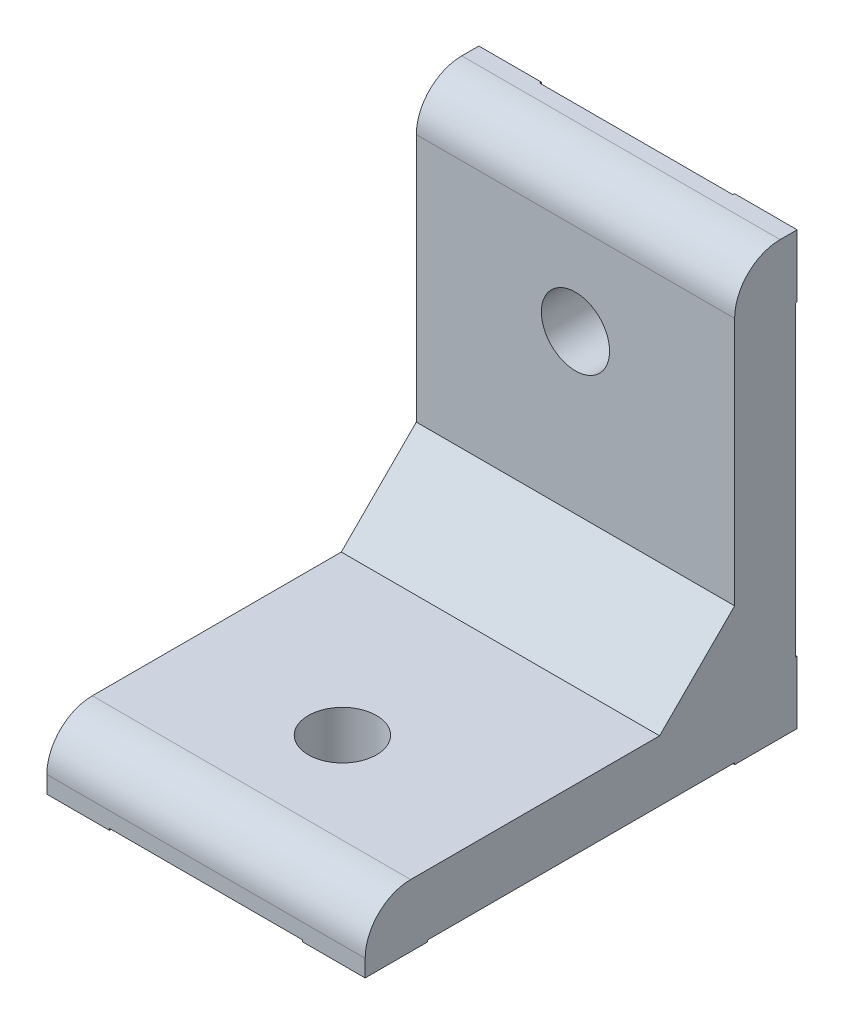
SolidWorks part; units mm, degrees
ref_plane "Plano frontal" through (0, 0, 0) normal (0, 0, 1) x (1, 0, 0)
ref_plane "Plano superior" through (0, 0, 0) normal (0, 1, 0) x (1, 0, 0)
ref_plane "Plano direito" through (0, 0, 0) normal (1, 0, 0) x (0, 0, -1)
sketch "Esboço1" plane through (0, 0, 0) normal (0, 0, 1) x (1, 0, 0)
  line L1 (-31.1337, 21.9882) -> (-3.1337, 21.9882)
  line L2 (-31.1337, 21.9882) -> (-31.1337, -16.0118)
  line L3 (-31.1337, -16.0118) -> (-3.1337, -16.0118)
  line L4 (-3.1337, 21.9882) -> (-3.1337, -16.0118)
extrude "Ressalto-extrusão1" add sketch "Esboço1" along normal blind 5.5
sketch "Esboço2" plane through (0, 0, 5.5) normal (0, 0, 1) x (1, 0, 0)
  line L0 (-3.1337, -16.0118) -> (-3.1337, 21.9882) construction
  line L1 (-31.1337, -16.0118) -> (-3.1337, -16.0118)
  line L2 (-31.1337, -16.0118) -> (-31.1337, -10.5118)
  line L3 (-31.1337, -10.5118) -> (-3.1337, -10.5118)
  line L4 (-3.1337, -16.0118) -> (-3.1337, -10.5118)
extrude "Ressalto-extrusão2" add sketch "Esboço2" along normal blind 32.5
sketch "Esboço3" plane through (-31.1337, 0, 0) normal (-1, 0, 0) x (0, 0, 1)
  line L0 (1.5, 21.9882) -> (5.5, 21.9882)
  line L1 (5.5, 21.9882) -> (5.5, 17.9882)
  line L2 (34, -10.5118) -> (38, -10.5118)
  line L3 (38, -10.5118) -> (38, -14.5118)
  arc A0 (38, -14.5118) -> (34, -10.5118) centre (34, -14.5118) ccw
  arc A1 (5.5, 17.9882) -> (1.5, 21.9882) centre (1.5, 17.9882) ccw
  dimension "D2" = 4
extrude "Corte-extrusão1" cut sketch "Esboço3" against normal blind 28
sketch "Esboço4" plane through (-31.1337, 0, 0) normal (-1, 0, 0) x (0, 0, 1)
  line L0 (5.5, -10.5118) -> (12.1, -10.5118)
  line L1 (34, -10.5118) -> (5.5, -10.5118) construction
  line L2 (12.1, -10.5118) -> (5.5, -3.9118)
  line L3 (5.5, 17.9882) -> (5.5, -10.5118) construction
  line L4 (5.5, -3.9118) -> (5.5, -10.5118)
extrude "Ressalto-extrusão3" add sketch "Esboço4" against normal blind 28
sketch "Esboço5" plane through (0, -16.0118, 0) normal (0, -1, 0) x (1, 0, 0)
  line L0 (-25.6337, 0) -> (-8.6337, 0)
  line L1 (-31.1337, 38) -> (-31.1337, 0) construction
  line L2 (-31.1337, 5.5) -> (-25.6337, 5.5) construction
  line L3 (-3.1337, 38) -> (-3.1337, 0) construction
  line L4 (-3.1337, 5.5) -> (-3.1337, 32.5)
  line L5 (-31.1337, 0) -> (-3.1337, 0) construction
  line L6 (-8.6337, 0) -> (-8.6337, 5.5) construction
  line L7 (-31.1337, 38) -> (-3.1337, 38) construction
  line L8 (-8.6337, 38) -> (-25.6337, 38)
  line L9 (-25.6337, 0) -> (-25.6337, 5.5) construction
  line L10 (-31.1337, 32.5) -> (-31.1337, 5.5)
  line L11 (-31.1337, 32.5) -> (-25.6337, 32.5) construction
  line L12 (-8.6337, 5.5) -> (-3.1337, 5.5) construction
  line L13 (-25.6337, 32.5) -> (-25.6337, 38) construction
  line L14 (-8.6337, 32.5) -> (-3.1337, 32.5) construction
  line L15 (-8.6337, 32.5) -> (-8.6337, 38) construction
  line L17 (-25.6337, 0) -> (-8.6337, 0)
  line L18 (-31.1337, 5.5) -> (-31.1337, 32.5)
  line L19 (-25.6337, 38) -> (-8.6337, 38)
  line L20 (-3.1337, 5.5) -> (-3.1337, 32.5)
  line L23 (-3.1337, 5.5) -> (-8.6337, 5.5)
  line L24 (-8.6337, 0) -> (-8.6337, 5.5)
  line L25 (-25.6337, 5.5) -> (-31.1337, 5.5)
  line L26 (-25.6337, 5.5) -> (-25.6337, 0)
  line L29 (-25.6337, 32.5) -> (-31.1337, 32.5)
  line L30 (-25.6337, 32.5) -> (-25.6337, 38)
  line L33 (-8.6337, 32.5) -> (-3.1337, 32.5)
  line L34 (-8.6337, 32.5) -> (-8.6337, 38)
  line M6 (-31.1337, 0) -> (-3.1337, 0)
  line M7 (-3.1337, 0) -> (-3.1337, 38)
  line M8 (-3.1337, 38) -> (-31.1337, 38)
  line M9 (-31.1337, 38) -> (-31.1337, 0)
extrude "Corte-extrusão2" cut sketch "Esboço5" against normal blind 0.15 contours L33 L34 L30 L29 L25 L26 L24 L23 M8 M9 M6 M7
sketch "Esboço6" plane through (0, 0, 0) normal (0, 0, -1) x (-1, 0, 0)
  line L0 (8.6337, -16.0118) -> (25.6337, -16.0118)
  line L3 (3.1337, -10.5118) -> (8.6337, -10.5118)
  line L4 (8.6337, -16.0118) -> (8.6337, -10.5118)
  line L7 (31.1337, -10.5118) -> (25.6337, -10.5118)
  line L8 (25.6337, -16.0118) -> (25.6337, -10.5118)
  line L9 (8.6337, -16.0118) -> (25.6337, -16.0118)
  line L10 (8.6337, 21.9882) -> (25.6337, 21.9882)
  line L13 (3.1337, 16.4882) -> (8.6337, 16.4882)
  line L14 (8.6337, 21.9882) -> (8.6337, 16.4882)
  line L17 (31.1337, 16.4882) -> (25.6337, 16.4882)
  line L18 (25.6337, 21.9882) -> (25.6337, 16.4882)
  line L19 (31.1337, 16.4882) -> (31.1337, -10.5118)
  line L20 (3.1337, -10.5118) -> (3.1337, 16.4882)
  line M11 (8.6337, -15.8618) -> (25.6337, -15.8618)
  line M14 (31.1337, -16.0118) -> (31.1337, 21.9882)
  line M15 (31.1337, 21.9882) -> (3.1337, 21.9882)
  line M16 (3.1337, 21.9882) -> (3.1337, -16.0118)
extrude "Corte-extrusão3" cut sketch "Esboço6" against normal blind 0.15 contours L18 L14 L13 L3 L4 L8 L7 L17 M15 M16 M11 M14
sketch "Esboço8" plane through (0, -15.8618, 0) normal (0, -1, 0) x (1, 0, 0)
  line L0 (-17.1337, 38) -> (-17.1337, 26) construction
  line L1 (-8.6337, 38) -> (-25.6337, 38) construction
  circle A0 centre (-17.1337, 26) radius 3
extrude "Corte-extrusão4" cut sketch "Esboço8" against normal blind 6
sketch "Esboço9" plane through (0, 0, 0.15) normal (0, 0, -1) x (-1, 0, 0)
  line L0 (17.1337, 21.9882) -> (17.1337, 9.9882) construction
  line L1 (25.6337, 21.9882) -> (8.6337, 21.9882) construction
  circle A0 centre (17.1337, 9.9882) radius 3
extrude "Corte-extrusão5" cut sketch "Esboço9" against normal blind 6
